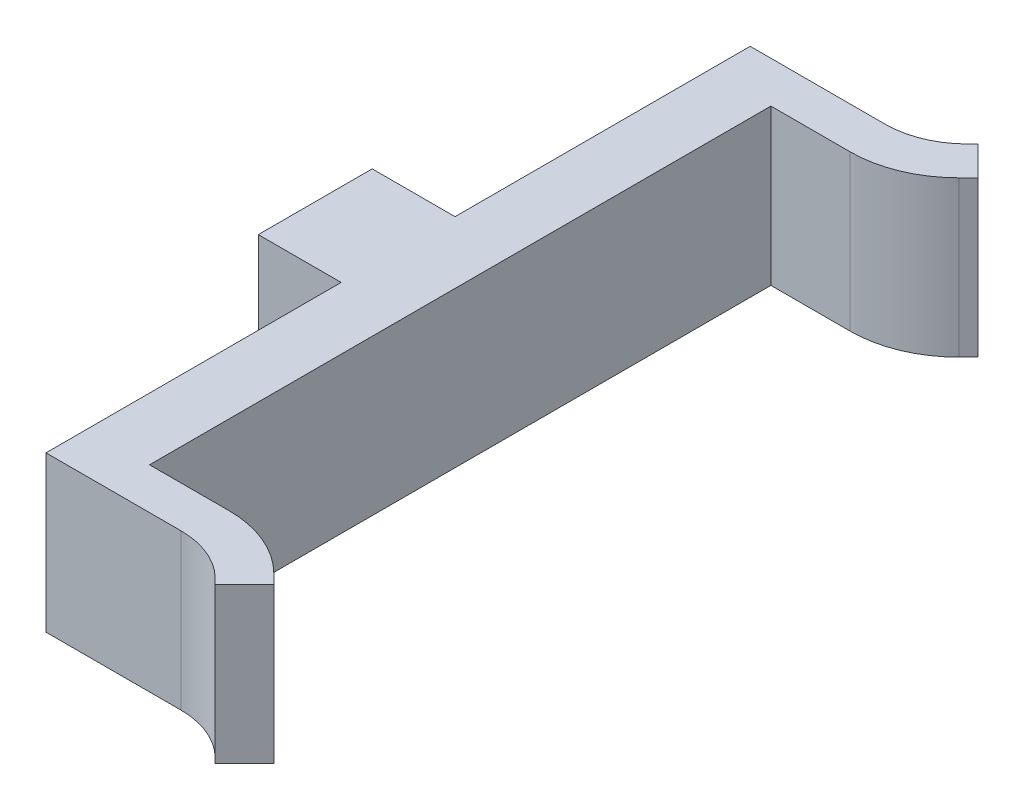
SolidWorks part; units mm, degrees
ref_plane "Front Plane" through (0, 0, 0) normal (0, 0, 1) x (1, 0, 0)
ref_plane "Top Plane" through (0, 0, 0) normal (0, 1, 0) x (1, 0, 0)
ref_plane "Right Plane" through (0, 0, 0) normal (1, 0, 0) x (0, 0, -1)
sketch "Sketch1" plane through (0, 0, 0) normal (0, 1, 0) x (1, 0, 0)
  line L0 (0, -34) -> (0, 34)
  line L1 (0, 34) -> (13.0294, 34)
  line L2 (18.6863, 36.3431) -> (19.1716, 36.8284)
  line L3 (19.1716, 36.8284) -> (22, 34)
  line L4 (22, 34) -> (21.0754, 33.0754)
  line L5 (13.6508, 30) -> (6, 30)
  line L6 (6, 30) -> (6, -30)
  line L7 (6, 0) -> (0, 0)
  line L8 (0, -34) -> (13.0294, -34)
  line L9 (18.6863, -36.3431) -> (19.1716, -36.8284)
  line L10 (19.1716, -36.8284) -> (22, -34)
  line L11 (22, -34) -> (21.0754, -33.0754)
  line L12 (13.6508, -30) -> (6, -30)
  arc A0 (21.0754, 33.0754) -> (13.6508, 30) centre (13.6508, 40.5) cw
  arc A1 (13.0294, 34) -> (18.6863, 36.3431) centre (13.0294, 42) ccw
  arc A2 (13.0294, -34) -> (18.6863, -36.3431) centre (13.0294, -42) cw
  arc A3 (21.0754, -33.0754) -> (13.6508, -30) centre (13.6508, -40.5) ccw
  point P11 (18, 30)
  dimension "D6" = 16
  dimension "D8" = 10.5
  dimension "D9" = 8
  dimension "D1" = 6
  dimension "D2" = 30
  dimension "D3" = 4
  dimension "D4" = 4
  dimension "D5" = 135
  dimension "D7" = 12
extrude "Boss-Extrude2" add sketch "Sketch1" along normal blind 15 contours A1 L1 L0 L7 L6 L5 A0 L4 L3 L2 | L11 A3 L12 L6 L7 L0 L8 A2 L9 L10
sketch "Sketch3" plane through (0, 0, 0) normal (-1, 0, 0) x (0, 0, 1)
  line L0 (-34, 0) -> (34, 15)
  line L1 (34, 0) -> (-34, 15)
  line L2 (-5.5, 3) -> (-5.5, 12)
  line L3 (-5.5, 3) -> (5.5, 3)
  line L4 (-34, 0) -> (34, 0)
  line L5 (34, 0) -> (34, 15)
  line L6 (34, 15) -> (-34, 15)
  line L7 (-34, 15) -> (-34, 0)
  line L8 (-34, 0) -> (34, 0)
  line L9 (34, 0) -> (34, 15)
  line L10 (34, 15) -> (-34, 15)
  line L11 (-34, 15) -> (-34, 0)
  line L12 (-5.5, 12) -> (5.5, 12)
  line L13 (5.5, 3) -> (5.5, 12)
  line L14 (-5.5, 3) -> (5.5, 12) construction
  line L15 (-5.5, 12) -> (5.5, 3) construction
  point P5 (0, 7.5)
  point P7 (0, 7.5)
  dimension "D2" = 11
  dimension "D3" = 9
  dimension "D1" = 0
extrude "Boss-Extrude3" add sketch "Sketch3" along normal blind 8 contours L3 L13 L1 L0 L2 | L0 L13 L12 L2 L1 | L2 L0 L1 | L1 L13 L0
sketch "Sketch4" plane through (-8, 0, 0) normal (-1, 0, 0) x (0, 0, 1)
  line L0 (-5.5, 12) -> (5.5, 3)
  line L1 (5.5, 12) -> (-5.5, 3)
  line L2 (1.8296, 9.75) -> (1.8296, 5.25)
  line L3 (0, 7.5) -> (0, 10.7515) construction
  line L4 (5.5, 3) -> (5.5, 12)
  line L5 (5.5, 12) -> (-5.5, 12)
  line L6 (-5.5, 12) -> (-5.5, 3)
  line L7 (-5.5, 3) -> (5.5, 3)
  line L8 (5.5, 3) -> (5.5, 12)
  line L9 (5.5, 12) -> (-5.5, 12)
  line L10 (-5.5, 12) -> (-5.5, 3)
  line L11 (-5.5, 3) -> (5.5, 3)
  line L12 (-1.8296, 9.75) -> (-1.8296, 5.25)
  line L13 (-1.9296, 9.7971) -> (-1.9296, 5.2029)
  line L14 (1.9296, 9.7971) -> (1.9296, 5.2029)
  arc A0 (1.8296, 9.75) -> (-1.8296, 9.75) centre (0, 7.5) ccw
  arc A1 (-1.8296, 5.25) -> (1.8296, 5.25) centre (0, 7.5) ccw
  arc A2 (1.9296, 9.7971) -> (-1.9296, 9.7971) centre (0, 7.5) ccw
  arc A3 (-1.9296, 5.2029) -> (1.9296, 5.2029) centre (0, 7.5) ccw
  dimension "D2" = 5.8
  dimension "D3" = 4.5
  dimension "D4" = 0.1
  dimension "D1" = 0
extrude "Cut-Extrude3" cut sketch "Sketch4" against normal blind 8 contours L13 A3 L14 A2
fillet "Fillet1" radius 0.3 4 edges at (-8, 10.5, 0) (-8, 7.5, -1.9296) (-8, 4.5, 0) (-8, 7.5, 1.9296)
sketch "Sketch5" plane through (0, 3, 0) normal (0, -1, 0) x (1, 0, 0)
  line L4 (0, -5.5) -> (0, 5.5)
  line L5 (0, 5.5) -> (-8, 5.5)
  line L6 (-8, 5.5) -> (-8, -5.5)
  line L7 (-8, -5.5) -> (0, -5.5)
  line L8 (0, -5.5) -> (0, 5.5)
  line L9 (0, 5.5) -> (-8, 5.5)
  line L10 (-8, 5.5) -> (-8, -5.5)
  line L11 (-8, -5.5) -> (0, -5.5)
  dimension "D1" = 0
extrude "Boss-Extrude4" add sketch "Sketch5" along normal blind 3
sketch "Sketch6" plane through (0, 12, 0) normal (0, 1, 0) x (1, 0, 0)
  line L4 (0, -5.5) -> (0, 5.5)
  line L5 (0, 5.5) -> (-8, 5.5)
  line L6 (-8, 5.5) -> (-8, -5.5)
  line L7 (-8, -5.5) -> (0, -5.5)
  line L8 (0, -5.5) -> (0, 5.5)
  line L9 (0, 5.5) -> (-8, 5.5)
  line L10 (-8, 5.5) -> (-8, -5.5)
  line L11 (-8, -5.5) -> (0, -5.5)
  dimension "D1" = 0
extrude "Boss-Extrude5" add sketch "Sketch6" along normal blind 3
